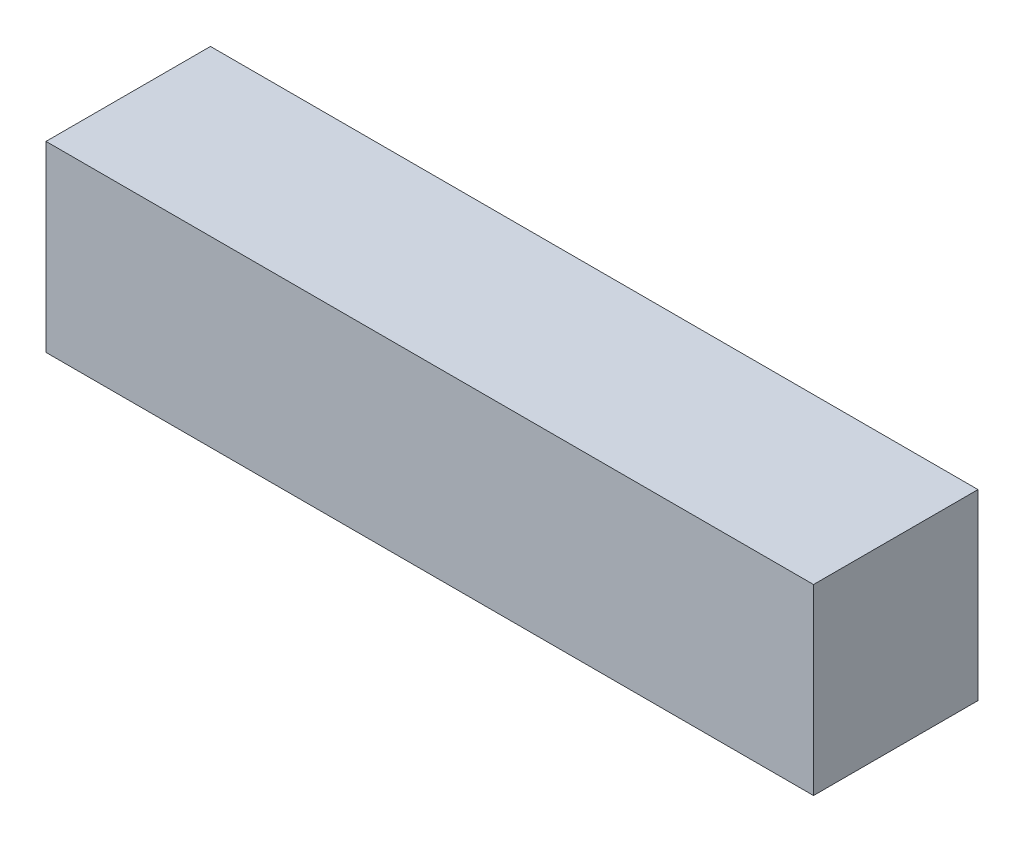
SolidWorks part; units mm, degrees
ref_plane "前视" through (0, 0, 0) normal (0, 0, 1) x (1, 0, 0)
ref_plane "上视" through (0, 0, 0) normal (0, 1, 0) x (1, 0, 0)
ref_plane "右视" through (0, 0, 0) normal (1, 0, 0) x (0, 0, -1)
sketch "草图1" plane through (0, 0, 0) normal (0, 0, 1) x (1, 0, 0)
  line L1 (0, 166.7) -> (700, 166.7)
  line L2 (0, 166.7) -> (0, 0)
  line L3 (0, 0) -> (700, 0)
  line L4 (700, 166.7) -> (700, 0)
  dimension "D1" = 700
  dimension "D2" = 166.7
extrude "基体-拉伸" add sketch "草图1" along normal blind 150
